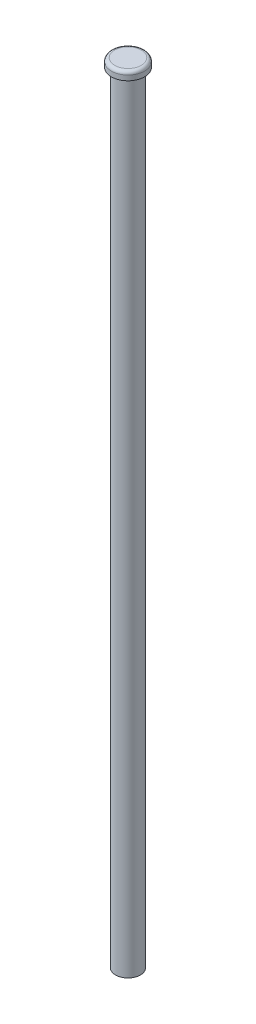
SolidWorks part; units mm, degrees
material "Cast Carbon Steel"
ref_plane "Front Plane" through (0, 0, 0) normal (0, 0, 1) x (1, 0, 0)
ref_plane "Top Plane" through (0, 0, 0) normal (0, 1, 0) x (1, 0, 0)
ref_plane "Right Plane" through (0, 0, 0) normal (1, 0, 0) x (0, 0, -1)
sketch "Sketch1" plane through (0, 0, 0) normal (0, 1, 0) x (1, 0, 0)
  circle A0 centre (0, 0) radius 1.5
extrude "Boss-Extrude1" add sketch "Sketch1" along normal blind 94
sketch "Sketch2" plane through (0, 94, 0) normal (0, 1, 0) x (1, 0, 0)
  circle A0 centre (0, 0) radius 2
extrude "Boss-Extrude2" add sketch "Sketch2" along normal blind 1
fillet "Fillet1" radius 0.4 1 edges at (0, 95, 2)
